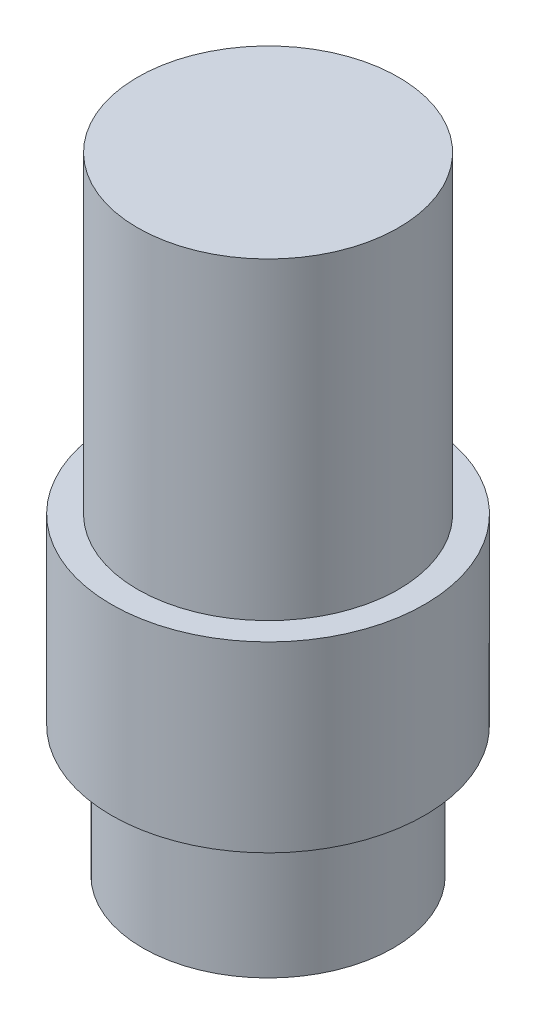
SolidWorks part; units mm, degrees
ref_plane "Front Plane" through (0, 0, 0) normal (0, 0, 1) x (1, 0, 0)
ref_plane "Top Plane" through (0, 0, 0) normal (0, 1, 0) x (1, 0, 0)
ref_plane "Right Plane" through (0, 0, 0) normal (1, 0, 0) x (0, 0, -1)
sketch "Sketch1" plane through (0, 0, 0) normal (0, 1, 0) x (1, 0, 0)
  circle A0 centre (0, 0) radius 2.4
  dimension "D1" = 4.8
extrude "Boss-Extrude1" add sketch "Sketch1" along normal blind 2.5
sketch "Sketch2" plane through (0, 2.5, 0) normal (0, 1, 0) x (1, 0, 0)
  circle A0 centre (0, 0) radius 3
  dimension "D1" = 6
extrude "Boss-Extrude2" add sketch "Sketch2" along normal blind 3.5 contours A0
sketch "Sketch3" plane through (0, 6, 0) normal (0, 1, 0) x (1, 0, 0)
  circle A0 centre (0, 0) radius 2.5
  dimension "D1" = 5
extrude "Boss-Extrude3" add sketch "Sketch3" along normal blind 6
